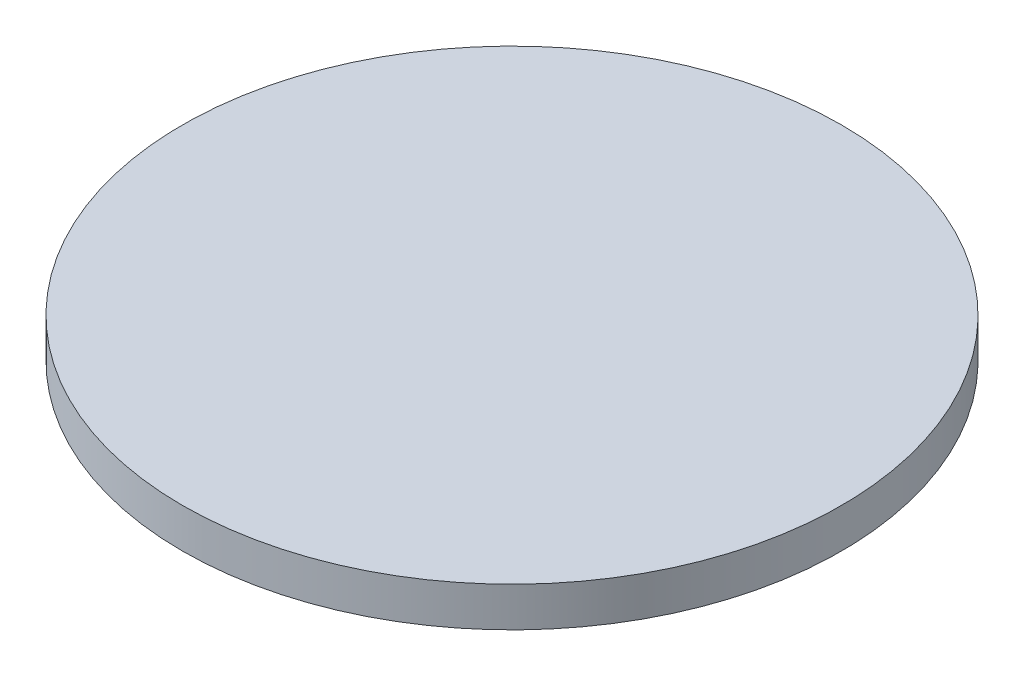
SolidWorks part; units mm, degrees
material "Acrilico (impatto medio-alto)"
ref_plane "Piano frontale" through (0, 0, 0) normal (0, 0, 1) x (1, 0, 0)
ref_plane "Piano superiore" through (0, 0, 0) normal (0, 1, 0) x (1, 0, 0)
ref_plane "Piano destro" through (0, 0, 0) normal (1, 0, 0) x (0, 0, -1)
sketch "Schizzo1" plane through (0, 0, 0) normal (0, 1, 0) x (1, 0, 0)
  circle A0 centre (0, 0) radius 50
  dimension "D1" = 100
extrude "Estrusione-Estrusione1" add sketch "Schizzo1" along normal blind 6
